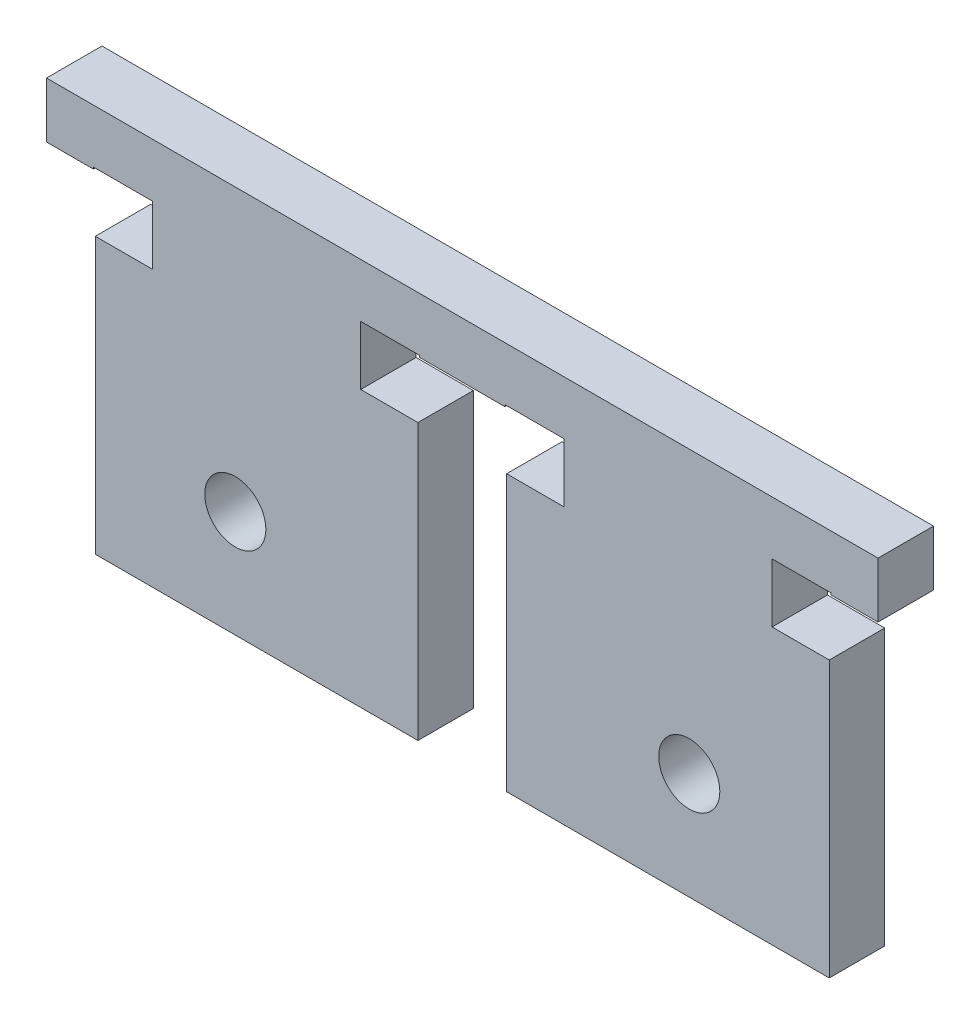
SolidWorks part; units mm, degrees
material "AISI 4130 Steel, annealed at 865C"
ref_plane "X-Y Datum" through (0, 0, 0) normal (0, 0, 1) x (1, 0, 0)
ref_plane "X-Z Datum" through (0, 0, 0) normal (0, 1, 0) x (1, 0, 0)
ref_plane "Y-Z Datum" through (0, 0, 0) normal (1, 0, 0) x (0, 0, -1)
sketch "Sketch3" plane through (0, 0, 0) normal (0, 0, 1) x (1, 0, 0)
  line L1 (-47.625, -30.48) -> (47.625, -30.48)
  line L2 (-47.625, -30.48) -> (-47.625, 30.48)
  line L3 (-47.625, 30.48) -> (47.625, 30.48)
  line L4 (47.625, -30.48) -> (47.625, 30.48)
  line L5 (-47.625, -30.48) -> (47.625, 30.48) construction
  line L6 (-47.625, 30.48) -> (47.625, -30.48) construction
  point P0 (0, 0)
  dimension "D1" = 95.25
  dimension "D2" = 60.96
extrude "Boss-Extrude1" add sketch "Sketch3" along normal blind 6.35
sketch "Sketch4" plane through (0, 0, 6.35) normal (0, 0, 1) x (1, 0, 0)
  line L0 (-47.625, 15.24) -> (-42.037, 15.24)
  line L1 (-47.625, 30.48) -> (-47.625, -30.48) construction
  line L2 (-42.037, 15.24) -> (-5.5245, 15.24)
  line L3 (-5.5245, 15.24) -> (5.5245, 15.24)
  line L4 (5.5245, 15.24) -> (42.037, 15.24)
  line L5 (42.037, 15.24) -> (47.625, 15.24)
  line L6 (47.625, -30.48) -> (47.625, 30.48) construction
  line L7 (0, 15.24) -> (0, -30.48) construction
  line L8 (-42.037, 15.24) -> (-47.625, 15.24)
  line L9 (-42.037, 15.24) -> (-42.037, -30.48)
  line L10 (-42.037, -30.48) -> (-47.625, -30.48)
  line L11 (-47.625, 15.24) -> (-47.625, -30.48)
  line L12 (-47.625, -30.48) -> (47.625, -30.48) construction
  line L17 (-5.5245, 15.24) -> (5.5245, 15.24)
  line L19 (-5.08, -30.48) -> (5.08, -30.48)
  line L20 (-5.08, -30.48) -> (-5.08, 15.24)
  line L25 (-5.08, 15.24) -> (5.08, 15.24)
  line L26 (5.08, -30.48) -> (5.08, 15.24)
  line L27 (42.037, 15.24) -> (47.625, 15.24)
  line L28 (42.037, 15.24) -> (42.037, -30.48)
  line L29 (42.037, -30.48) -> (47.625, -30.48)
  line L31 (-5.08, -30.48) -> (5.08, 15.24) construction
  line L32 (-5.08, 15.24) -> (5.08, -30.48) construction
  point P15 (0, -7.62)
  point P20 (0, -7.62)
  dimension "D2" = 36.5125
  dimension "D3" = 5.588
  dimension "D4" = 36.5125
  dimension "D5" = 10.16
  dimension "D6" = 22.86
  dimension "D7" = 47.625
  dimension "D8" = 45.72
  dimension "D9" = 45.72
extrude "Cut-Extrude1" cut sketch "Sketch4" against normal blind 6.35
sketch "Sketch5" plane through (0, 0, 6.35) normal (0, 0, 1) x (1, 0, 0)
  line L0 (-42.2402, 15.4432) -> (-35.4838, 15.4432)
  line L9 (-42.037, 15.24) -> (-5.08, 15.24)
  line L14 (-35.4838, 15.4432) -> (-35.4838, 8.6868)
  line L15 (-42.2402, 8.6868) -> (-35.4838, 8.6868)
  line L24 (-42.2402, 15.4432) -> (-42.2402, 8.6868)
  line L25 (-4.8768, 15.4432) -> (-4.8768, 8.6868)
  line L26 (-42.037, 15.24) -> (-35.687, 15.24)
  line L27 (-42.037, 15.24) -> (-42.037, 8.89)
  line L28 (-42.037, 8.89) -> (-35.687, 8.89)
  line L29 (-35.687, 15.24) -> (-35.687, 8.89)
  line L30 (-5.08, 15.24) -> (-11.43, 15.24)
  line L31 (-5.08, 15.24) -> (-5.08, 8.89)
  line L32 (-5.08, 8.89) -> (-11.43, 8.89)
  line L33 (-11.43, 15.24) -> (-11.43, 8.89)
  line L34 (-4.8768, 8.6868) -> (-11.6332, 8.6868)
  line L35 (-11.6332, 15.4432) -> (-11.6332, 8.6868)
  line L36 (-4.8768, 15.4432) -> (-11.6332, 15.4432)
  dimension "D1" = 6.35
  dimension "D2" = 6.35
  dimension "D3" = 6.35
  dimension "D4" = 0.2032
  dimension "D5" = 0.2032
extrude "Cut-Extrude2" cut sketch "Sketch5" against normal through all
mirror "Mirror1" about plane through (0, 0, 0) normal (1, 0, 0) of "Cut-Extrude2"
sketch "Sketch8" [suppressed] plane through (0, 15.24, 0) normal (0, -1, 0) x (1, 0, 0)
  line L0 (-9.525, 3.175) -> (9.525, 3.175) construction
  line L1 (-9.525, 0) -> (-9.525, 6.35) construction
  line L2 (9.525, 0) -> (9.525, 6.35) construction
  line L3 (-4.7625, 6.35) -> (4.7625, 6.35) construction
  line L4 (-4.7625, 0) -> (4.7625, 0)
  line L5 (-4.7625, 0) -> (-4.7625, 6.35)
  line L6 (-4.7625, 6.35) -> (4.7625, 6.35)
  line L7 (4.7625, 0) -> (4.7625, 6.35)
  line L8 (-4.7625, 0) -> (4.7625, 6.35) construction
  line L9 (-4.7625, 6.35) -> (4.7625, 0) construction
  point P6 (0, 3.175)
  line M3 (-4.7625, 0) -> (4.7625, 0)
  dimension "D1" = 4.7625
extrude "Cut-Extrude3" [suppressed] cut sketch "Sketch8" against normal blind 1.5875 contours L7 L0 L5 M3
sketch "Sketch9" plane through (0, 30.48, 0) normal (0, 1, 0) x (1, 0, 0)
  line L1 (-47.625, 0) -> (47.625, 0)
  line L2 (-47.625, 0) -> (-47.625, -6.35)
  line L3 (-47.625, -6.35) -> (47.625, -6.35)
  line L4 (47.625, 0) -> (47.625, -6.35)
extrude "Cut-Extrude6" cut sketch "Sketch9" against normal blind 8.89
sketch "Sketch10" plane through (0, 0, 6.35) normal (0, 0, 1) x (1, 0, 0)
  line L0 (0, 0) -> (0, -30.2463) construction
  line L1 (-26, -10.6279) -> (26, -10.6279) construction
  circle A1 centre (-26, -10.6279) radius 3.3015
  circle A3 centre (26, -10.6279) radius 3.3015
  point P2 (26, -10.6279)
  point P10 (-26, -10.6279)
  point P21 (-26, -10.6279)
  point P23 (26, -10.6279)
  dimension "D2" = 6.603
  dimension "D1" = 52
sketch "Sketch11" plane through (0, -30.48, 0) normal (0, -1, 0) x (1, 0, 0)
  line L1 (-42.037, 6.35) -> (42.037, 6.35)
  line L2 (-42.037, 6.35) -> (-42.037, 0)
  line L3 (-42.037, 0) -> (42.037, 0)
  line L4 (42.037, 6.35) -> (42.037, 0)
extrude "Cut-Extrude9" cut sketch "Sketch11" against normal blind 7.62
hole_wizard "M6 Clearance Hole2" positions "Sketch10" profile "Sketch12" hole size "M6" standard "ANSI Metric" end condition through all
sketch "Sketch12" plane through (26, -10.6279, 6.35) normal (1, 0, 0) x (0, -1, 0)
  line L0 (0, 0) -> (0, 6.35)
  line L1 (0, 6.35) -> (3.5, 6.35)
  line L2 (3.5, 6.35) -> (3.5, 0)
  line L5 (3.5, 0) -> (0, 0)
  line L11 (0, -6.35) -> (0, 107.95) construction
  dimension "Thru Hole Dia." = 7
  dimension "Thru Hole Depth" = 6.35
